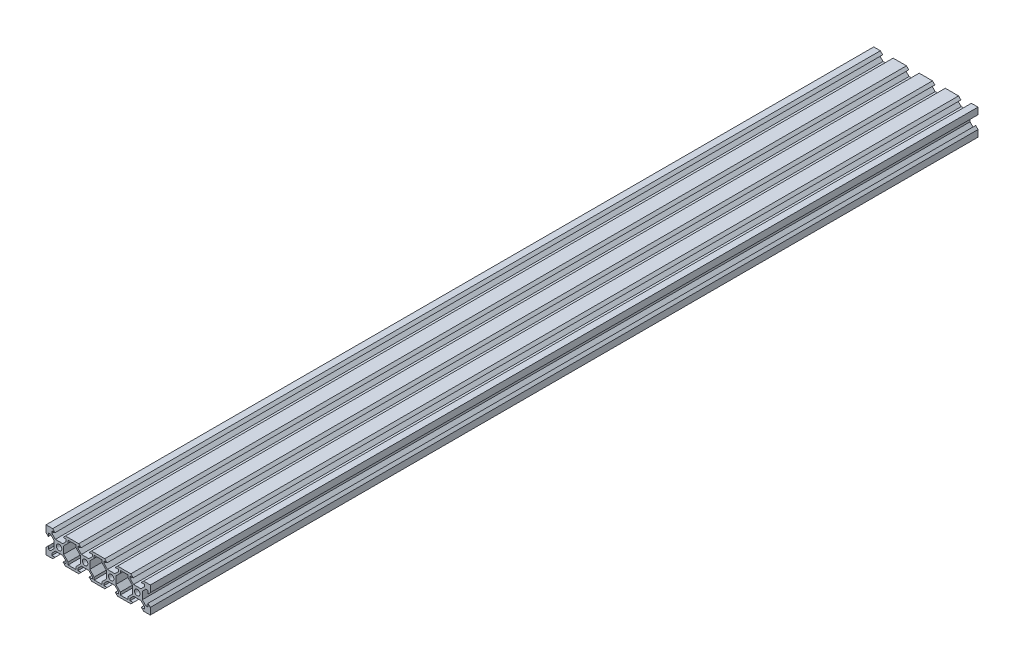
SolidWorks part; units mm, degrees
ref_plane "Plan de face" through (0, 0, 0) normal (0, 0, 1) x (1, 0, 0)
ref_plane "Plan de dessus" through (0, 0, 0) normal (0, 1, 0) x (1, 0, 0)
ref_plane "Plan de droite" through (0, 0, 0) normal (1, 0, 0) x (0, 0, -1)
sketch "Esquisse1" plane through (0, 0, 0) normal (0, 0, 1) x (1, 0, 0)
  line L45 (-65.6277, 8.2661) -> (14.3723, 8.2661)
  line L46 (-65.6277, 8.2661) -> (-65.6277, -11.7339)
  line L47 (-65.6277, -11.7339) -> (14.3723, -11.7339)
  line L48 (14.3723, 8.2661) -> (14.3723, -11.7339)
  dimension "D1" = 80
  dimension "D2" = 20
extrude "Boss.-Extru.1" add sketch "Esquisse1" along normal blind 635
sketch "Esquisse2" plane through (0, 0, 0) normal (0, 0, -1) x (-1, 0, 0)
  line L0 (-14.3723, -11.7339) -> (-14.3723, 8.2661) construction
  line L2 (50.7277, 8.2661) -> (60.5277, 8.2661)
  line L3 (-14.3723, 8.2661) -> (65.6277, 8.2661) construction
  line L4 (60.5277, 8.2661) -> (58.7277, 6.4661)
  line L5 (58.7277, 6.4661) -> (61.1277, 6.4661)
  line L6 (61.1277, 6.4661) -> (61.1277, 4.8261)
  line L7 (61.1277, 4.8261) -> (58.4677, 2.1661)
  line L8 (58.4677, 2.1661) -> (52.7877, 2.1661)
  line L9 (52.7877, 2.1661) -> (50.1277, 4.8261)
  line L10 (50.1277, 4.8261) -> (50.1277, 6.4661)
  line L11 (50.1277, 6.4661) -> (52.5277, 6.4661)
  line L12 (52.5277, 6.4661) -> (50.7277, 8.2661)
  line L43 (65.6277, 8.2661) -> (65.6277, -11.7339) construction
  line L44 (65.6277, 3.1661) -> (65.6277, -6.6339)
  line L45 (65.6277, -6.6339) -> (63.8277, -4.8339)
  line L46 (63.8277, -4.8339) -> (63.8277, -7.2339)
  line L47 (63.8277, -7.2339) -> (62.1877, -7.2339)
  line L48 (62.1877, -7.2339) -> (59.5277, -4.5739)
  line L49 (59.5277, -4.5739) -> (59.5277, 1.1061)
  line L50 (59.5277, 1.1061) -> (62.1877, 3.7661)
  line L51 (62.1877, 3.7661) -> (63.8277, 3.7661)
  line L52 (63.8277, 3.7661) -> (63.8277, 1.3661)
  line L53 (63.8277, 1.3661) -> (65.6277, 3.1661)
  line L54 (60.5277, -11.7339) -> (50.7277, -11.7339)
  line L55 (50.7277, -11.7339) -> (52.5277, -9.9339)
  line L56 (52.5277, -9.9339) -> (50.1277, -9.9339)
  line L57 (50.1277, -9.9339) -> (50.1277, -8.2939)
  line L58 (50.1277, -8.2939) -> (52.7877, -5.6339)
  line L59 (52.7877, -5.6339) -> (58.4677, -5.6339)
  line L60 (58.4677, -5.6339) -> (61.1277, -8.2939)
  line L61 (61.1277, -8.2939) -> (61.1277, -9.9339)
  line L62 (61.1277, -9.9339) -> (58.7277, -9.9339)
  line L63 (58.7277, -9.9339) -> (60.5277, -11.7339)
  line L64 (55.6277, -1.7339) -> (58.4677, 2.1661) construction
  line L65 (55.6277, -1.7339) -> (59.5277, -4.5739) construction
  line L66 (30.7277, 8.2661) -> (40.5277, 8.2661)
  line L67 (40.5277, 8.2661) -> (38.7277, 6.4661)
  line L68 (38.7277, 6.4661) -> (41.1277, 6.4661)
  line L69 (41.1277, 6.4661) -> (41.1277, 4.8261)
  line L70 (41.1277, 4.8261) -> (38.4677, 2.1661)
  line L71 (38.4677, 2.1661) -> (32.7877, 2.1661)
  line L72 (32.7877, 2.1661) -> (30.1277, 4.8261)
  line L73 (30.1277, 4.8261) -> (30.1277, 6.4661)
  line L74 (30.1277, 6.4661) -> (32.5277, 6.4661)
  line L75 (32.5277, 6.4661) -> (30.7277, 8.2661)
  line L76 (40.5277, -11.7339) -> (30.7277, -11.7339)
  line L77 (30.7277, -11.7339) -> (32.5277, -9.9339)
  line L78 (32.5277, -9.9339) -> (30.1277, -9.9339)
  line L79 (30.1277, -9.9339) -> (30.1277, -8.2939)
  line L80 (30.1277, -8.2939) -> (32.7877, -5.6339)
  line L81 (32.7877, -5.6339) -> (38.4677, -5.6339)
  line L82 (38.4677, -5.6339) -> (41.1277, -8.2939)
  line L83 (41.1277, -8.2939) -> (41.1277, -9.9339)
  line L84 (41.1277, -9.9339) -> (38.7277, -9.9339)
  line L85 (38.7277, -9.9339) -> (40.5277, -11.7339)
  line L86 (35.6277, -1.7339) -> (38.4677, 2.1661) construction
  line L87 (10.7277, 8.2661) -> (20.5277, 8.2661)
  line L88 (20.5277, 8.2661) -> (18.7277, 6.4661)
  line L89 (18.7277, 6.4661) -> (21.1277, 6.4661)
  line L90 (21.1277, 6.4661) -> (21.1277, 4.8261)
  line L91 (21.1277, 4.8261) -> (18.4677, 2.1661)
  line L92 (18.4677, 2.1661) -> (12.7877, 2.1661)
  line L93 (12.7877, 2.1661) -> (10.1277, 4.8261)
  line L94 (10.1277, 4.8261) -> (10.1277, 6.4661)
  line L95 (10.1277, 6.4661) -> (12.5277, 6.4661)
  line L96 (12.5277, 6.4661) -> (10.7277, 8.2661)
  line L97 (20.5277, -11.7339) -> (10.7277, -11.7339)
  line L98 (10.7277, -11.7339) -> (12.5277, -9.9339)
  line L99 (12.5277, -9.9339) -> (10.1277, -9.9339)
  line L100 (10.1277, -9.9339) -> (10.1277, -8.2939)
  line L101 (10.1277, -8.2939) -> (12.7877, -5.6339)
  line L102 (12.7877, -5.6339) -> (18.4677, -5.6339)
  line L103 (18.4677, -5.6339) -> (21.1277, -8.2939)
  line L104 (21.1277, -8.2939) -> (21.1277, -9.9339)
  line L105 (21.1277, -9.9339) -> (18.7277, -9.9339)
  line L106 (18.7277, -9.9339) -> (20.5277, -11.7339)
  line L107 (15.6277, -1.7339) -> (18.4677, 2.1661) construction
  line L108 (-9.2723, 8.2661) -> (0.5277, 8.2661)
  line L109 (0.5277, 8.2661) -> (-1.2723, 6.4661)
  line L110 (-1.2723, 6.4661) -> (1.1277, 6.4661)
  line L111 (1.1277, 6.4661) -> (1.1277, 4.8261)
  line L112 (1.1277, 4.8261) -> (-1.5323, 2.1661)
  line L113 (-1.5323, 2.1661) -> (-7.2123, 2.1661)
  line L114 (-7.2123, 2.1661) -> (-9.8723, 4.8261)
  line L115 (-9.8723, 4.8261) -> (-9.8723, 6.4661)
  line L116 (-9.8723, 6.4661) -> (-7.4723, 6.4661)
  line L117 (-7.4723, 6.4661) -> (-9.2723, 8.2661)
  line L118 (0.5277, -11.7339) -> (-9.2723, -11.7339)
  line L119 (-9.2723, -11.7339) -> (-7.4723, -9.9339)
  line L120 (-7.4723, -9.9339) -> (-9.8723, -9.9339)
  line L121 (-9.8723, -9.9339) -> (-9.8723, -8.2939)
  line L122 (-9.8723, -8.2939) -> (-7.2123, -5.6339)
  line L123 (-7.2123, -5.6339) -> (-1.5323, -5.6339)
  line L124 (-1.5323, -5.6339) -> (1.1277, -8.2939)
  line L125 (1.1277, -8.2939) -> (1.1277, -9.9339)
  line L126 (1.1277, -9.9339) -> (-1.2723, -9.9339)
  line L127 (-1.2723, -9.9339) -> (0.5277, -11.7339)
  line L128 (-4.3723, -1.7339) -> (-1.5323, 2.1661) construction
  line L129 (-14.3723, -6.6339) -> (-14.3723, 3.1661)
  line L130 (-14.3723, 3.1661) -> (-12.5723, 1.3661)
  line L131 (-12.5723, 1.3661) -> (-12.5723, 3.7661)
  line L132 (-12.5723, 3.7661) -> (-10.9323, 3.7661)
  line L133 (-10.9323, 3.7661) -> (-8.2723, 1.1061)
  line L134 (-8.2723, 1.1061) -> (-8.2723, -4.5739)
  line L135 (-8.2723, -4.5739) -> (-10.9323, -7.2339)
  line L136 (-10.9323, -7.2339) -> (-12.5723, -7.2339)
  line L137 (-12.5723, -7.2339) -> (-12.5723, -4.8339)
  line L138 (-12.5723, -4.8339) -> (-14.3723, -6.6339)
  line L139 (-4.3723, -1.7339) -> (-1.5323, 2.1661) construction
  line L140 (-4.3723, -1.7339) -> (-8.2723, 1.1061) construction
  circle A0 centre (55.6277, -1.7339) radius 2.1
  circle A1 centre (35.6277, -1.7339) radius 2.1
  circle A2 centre (15.6277, -1.7339) radius 2.1
  circle A3 centre (-4.3723, -1.7339) radius 2.1
  point P5 (-14.3723, -1.7339)
  point P17 (55.6277, 2.1661)
  point P54 (10.6277, 13.2661)
  dimension "D1" = 4.2
  dimension "D2" = 135
  dimension "D3" = 1.64
  dimension "D4" = 5.68
  dimension "D5" = 1.8
  dimension "D6" = 6.2
  dimension "D7" = 11
  dimension "D8" = 10
  dimension "D10" = 90
  dimension "D13" = 90
  dimension "D11" = 4
  dimension "D9" = 3
  dimension "D12" = 2
extrude "Enlèv. mat.-Extru.1" cut sketch "Esquisse2" against normal up to next
sketch "Esquisse3" plane through (0, 0, 0) normal (0, 0, -1) x (-1, 0, 0)
  line L0 (2.6183, 6.4661) -> (8.6372, 6.4661)
  line L1 (8.6372, 6.4661) -> (8.6372, 4.5061)
  line L2 (8.6372, 4.5061) -> (12.0372, 1.1061)
  line L3 (12.0372, 1.1061) -> (12.0372, -4.5739)
  line L4 (12.0372, -4.5739) -> (8.6372, -7.9739)
  line L5 (8.6372, -7.9739) -> (8.6372, -9.9339)
  line L6 (8.6372, -9.9339) -> (2.6183, -9.9339)
  line L7 (2.6183, -9.9339) -> (2.6183, -7.9739)
  line L8 (2.6183, -7.9739) -> (-0.7817, -4.5739)
  line L9 (-0.7817, -4.5739) -> (-0.7817, 1.1061)
  line L10 (-0.7817, 1.1061) -> (2.6183, 4.5061)
  line L11 (2.6183, 4.5061) -> (2.6183, 6.4661)
  line L12 (0.5277, 8.2661) -> (10.7277, 8.2661) construction
  line L13 (-1.2723, -9.9339) -> (1.1277, -9.9339) construction
  line L14 (1.1277, 6.4661) -> (-1.2723, 6.4661) construction
  line L15 (22.6183, 6.4661) -> (28.6372, 6.4661)
  line L16 (28.6372, 6.4661) -> (28.6372, 4.5061)
  line L17 (28.6372, 4.5061) -> (32.0372, 1.1061)
  line L18 (32.0372, 1.1061) -> (32.0372, -4.5739)
  line L19 (32.0372, -4.5739) -> (28.6372, -7.9739)
  line L20 (28.6372, -7.9739) -> (28.6372, -9.9339)
  line L21 (28.6372, -9.9339) -> (22.6183, -9.9339)
  line L22 (22.6183, -9.9339) -> (22.6183, -7.9739)
  line L23 (22.6183, -7.9739) -> (19.2183, -4.5739)
  line L24 (19.2183, -4.5739) -> (19.2183, 1.1061)
  line L25 (19.2183, 1.1061) -> (22.6183, 4.5061)
  line L26 (22.6183, 4.5061) -> (22.6183, 6.4661)
  line L27 (42.6183, 6.4661) -> (48.6372, 6.4661)
  line L28 (48.6372, 6.4661) -> (48.6372, 4.5061)
  line L29 (48.6372, 4.5061) -> (52.0372, 1.1061)
  line L30 (52.0372, 1.1061) -> (52.0372, -4.5739)
  line L31 (52.0372, -4.5739) -> (48.6372, -7.9739)
  line L32 (48.6372, -7.9739) -> (48.6372, -9.9339)
  line L33 (48.6372, -9.9339) -> (42.6183, -9.9339)
  line L34 (42.6183, -9.9339) -> (42.6183, -7.9739)
  line L35 (42.6183, -7.9739) -> (39.2183, -4.5739)
  line L36 (39.2183, -4.5739) -> (39.2183, 1.1061)
  line L37 (39.2183, 1.1061) -> (42.6183, 4.5061)
  line L38 (42.6183, 4.5061) -> (42.6183, 6.4661)
  circle A0 centre (-4.3723, -1.7339) radius 2.1 construction
  circle A1 centre (-4.3723, -1.7339) radius 2.1 construction
  point P13 (5.6277, 6.4661)
  point P16 (5.6277, 8.2661)
  point P28 (-0.7817, -1.7339)
  point P29 (12.0372, -1.7339)
  dimension "D1" = 5.68
  dimension "D2" = 1.96
  dimension "D3" = 3
extrude "Enlèv. mat.-Extru.2" cut sketch "Esquisse3" against normal up to next
